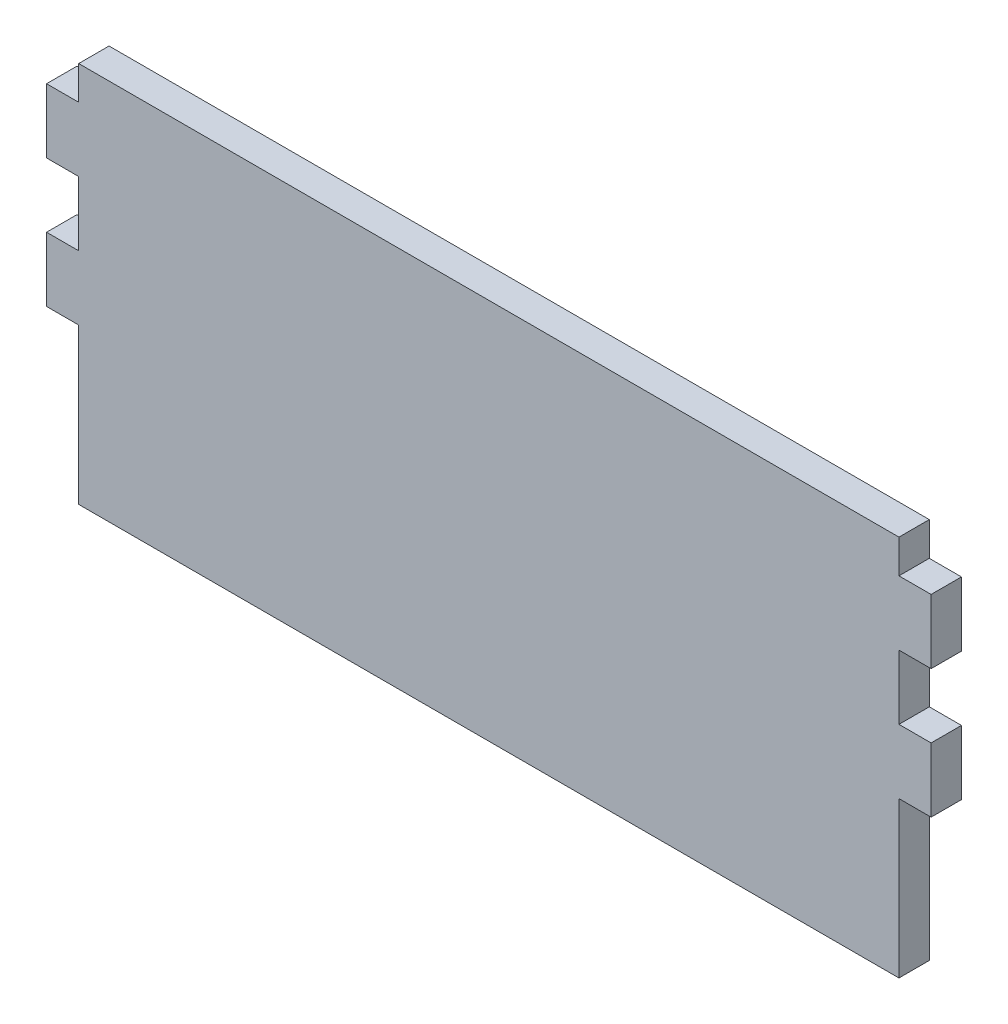
SolidWorks part; units mm, degrees
material "Acrylic (Medium-high impact)"
ref_plane "Front Plane" through (0, 0, 0) normal (0, 0, 1) x (1, 0, 0)
ref_plane "Top Plane" through (0, 0, 0) normal (0, 1, 0) x (1, 0, 0)
ref_plane "Right Plane" through (0, 0, 0) normal (1, 0, 0) x (0, 0, -1)
sketch "Sketch1" plane through (0, 0, 0) normal (0, 0, 1) x (1, 0, 0)
  line L0 (0, 0) -> (0, 15.3413)
  line L1 (0, 15.3413) -> (-3.175, 15.3413)
  line L2 (-3.175, 15.3413) -> (-3.175, 21.6913)
  line L3 (-3.175, 21.6913) -> (0, 21.6913)
  line L4 (0, 21.6913) -> (0, 28.0413)
  line L5 (0, 28.0413) -> (-3.175, 28.0413)
  line L6 (-3.175, 28.0413) -> (-3.175, 34.3913)
  line L7 (-3.175, 34.3913) -> (0, 34.3913)
  line L8 (40.5, 37.7058) -> (40.5, 0) construction
  line L9 (81, 0) -> (0, 0)
  line L10 (0, 34.3913) -> (0, 37.7058)
  line L11 (0, 37.7058) -> (81, 37.7058)
  line L12 (81, 34.3913) -> (81, 37.7058)
  line L13 (84.175, 34.3913) -> (81, 34.3913)
  line L14 (84.175, 28.0413) -> (84.175, 34.3913)
  line L15 (81, 28.0413) -> (84.175, 28.0413)
  line L16 (81, 21.6913) -> (81, 28.0413)
  line L17 (84.175, 21.6913) -> (81, 21.6913)
  line L18 (84.175, 15.3413) -> (84.175, 21.6913)
  line L19 (81, 15.3413) -> (84.175, 15.3413)
  line L20 (81, 0) -> (81, 15.3413)
  dimension "D1" = 40.5
  dimension "D2" = 3.175
  dimension "D3" = 6.35
  dimension "D4" = 15.3413
  dimension "D5" = 3.3145
extrude "Boss-Extrude1" add sketch "Sketch1" along normal blind 2.9972
